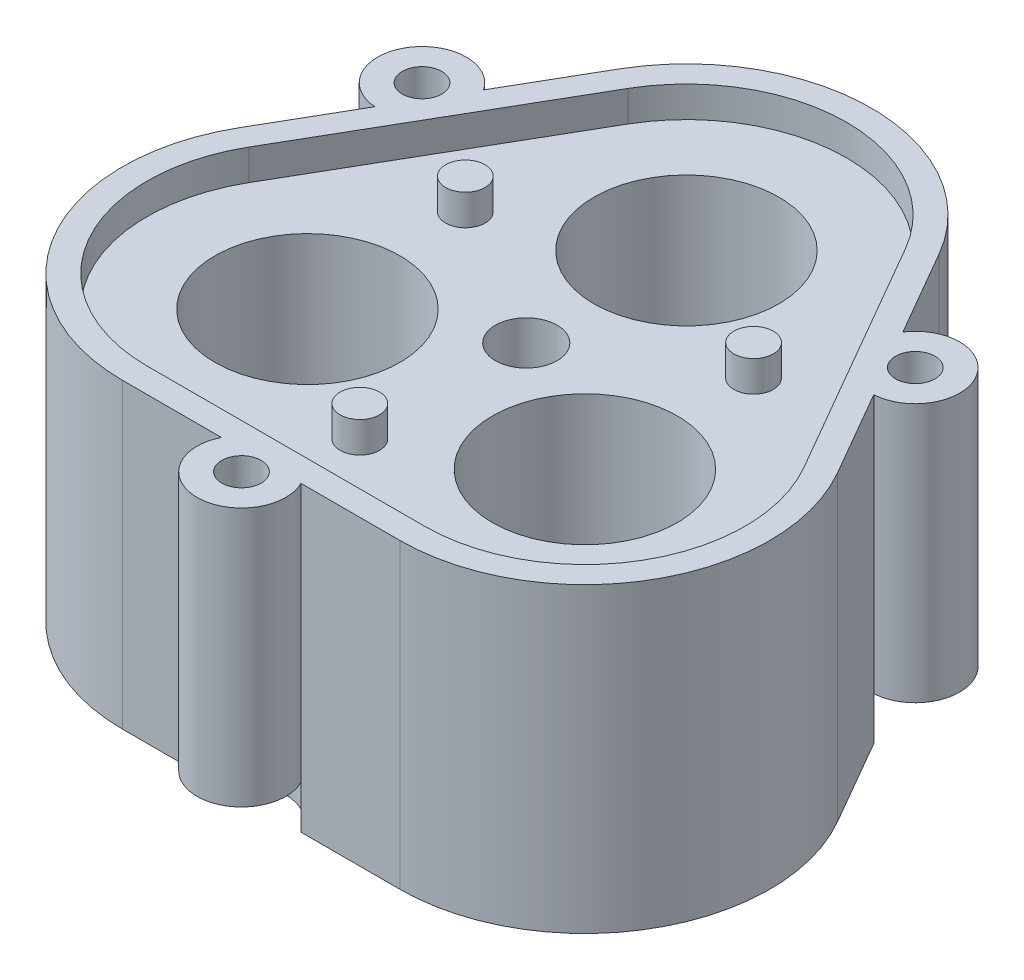
SolidWorks part; units mm, degrees
ref_plane "Front Plane" through (0, 0, 0) normal (0, 0, 1) x (1, 0, 0)
ref_plane "Top Plane" through (0, 0, 0) normal (0, 1, 0) x (1, 0, 0)
ref_plane "Right Plane" through (0, 0, 0) normal (1, 0, 0) x (0, 0, -1)
sketch "Sketch2" plane through (0, 0, 0) normal (0, 1, 0) x (1, 0, 0)
  line L0 (0, 0) -> (0, 12.9904) construction
  line L1 (0, 0) -> (11.25, -6.4952) construction
  line L2 (0, 0) -> (-11.25, -6.4952) construction
  line L3 (0, 12.9904) -> (-11.25, -6.4952) construction
  line L4 (-11.25, -6.4952) -> (11.25, -6.4952) construction
  line L5 (-11.25, -13.9952) -> (11.25, -13.9952) construction
  line L6 (6.4952, 16.7404) -> (17.7452, -2.7452) construction
  line L7 (-6.4952, 16.7404) -> (-17.7452, -2.7452) construction
  line L8 (-37.2308, -21.4952) -> (37.2308, -21.4952)
  line L9 (0, 42.9904) -> (-37.2308, -21.4952)
  line L10 (0, 42.9904) -> (37.2308, -21.4952)
  circle A0 centre (0, 12.9904) radius 7.5
  circle A1 centre (-11.25, -6.4952) radius 7.5
  circle A2 centre (11.25, -6.4952) radius 7.5
  circle A3 centre (0, 0) radius 2.5
  circle A4 centre (-11.25, -6.4952) radius 15 construction
  dimension "D3" = 15
  dimension "D9" = 5
  dimension "D10" = 30
  dimension "D1" = 120
  dimension "D2" = 120
  dimension "D4" = 22.5
  dimension "D5" = 7.5
  dimension "D6" = 7.5
  dimension "D7" = 7.5
  dimension "D8" = 74.4615
extrude "Boss-Extrude1" add sketch "Sketch2" along normal blind 12
sketch "Sketch4" plane through (0, 0, 0) normal (0, -1, 0) x (1, 0, 0)
  line L0 (-37.2308, 21.4952) -> (37.2308, 21.4952)
  line L1 (37.2308, 21.4952) -> (0, -42.9904)
  line L2 (0, -42.9904) -> (-37.2308, 21.4952)
  circle A0 centre (-11.25, 6.4952) radius 6
  circle A1 centre (11.25, 6.4952) radius 6
  circle A2 centre (0, -12.9904) radius 6
  circle A3 centre (0, 0) radius 2.5
  dimension "D1" = 12
  dimension "D2" = 5
extrude "Boss-Extrude2" add sketch "Sketch4" along normal blind 8
ref_plane "Plane1" through (0, -8, 0) normal (0, 1, 0) x (1, 0, 0)
sketch "Sketch7" plane through (0, -8, 0) normal (0, 1, 0) x (1, 0, 0)
  circle A0 centre (0, 12.9904) radius 4
  circle A1 centre (-11.25, -6.4952) radius 4
  circle A2 centre (11.25, -6.4952) radius 4
  dimension "D1" = 8
extrude "Boss-Extrude3" add sketch "Sketch7" along normal blind 8 separate body
sketch "Sketch9" plane through (0, -8, 0) normal (0, 1, 0) x (1, 0, 0)
  line L0 (0, 42.9904) -> (-37.2308, -21.4952)
  line L1 (-37.2308, -21.4952) -> (37.2308, -21.4952)
  line L2 (37.2308, -21.4952) -> (0, 42.9904)
extrude "Boss-Extrude4" add sketch "Sketch9" against normal blind 2
sketch "Sketch10" plane through (0, -8, 0) normal (0, 1, 0) x (1, 0, 0)
  line L0 (0, 0) -> (-11.25, -6.4952) construction
  line L1 (-11.25, -6.4952) -> (0, 12.9904) construction
  line L2 (0, 12.9904) -> (0, 0) construction
  line L3 (0, 0) -> (11.25, -6.4952) construction
  line L4 (11.25, -6.4952) -> (0, 12.9904) construction
  line L5 (-11.25, -6.4952) -> (11.25, -6.4952) construction
  line L6 (-11.25, -6.4952) -> (-12.6686, -1.7007) construction
  line L7 (-11.25, -6.4952) -> (-8.386, -2.3967) construction
  line L8 (-11.25, -6.4952) -> (-6.26, -6.179) construction
  line L9 (-11.25, -6.4952) -> (-7.8916, -10.1994) construction
  line L10 (-11.25, -6.4952) -> (-12.0521, -11.4304) construction
  line L11 (-11.25, -6.4952) -> (-15.6086, -8.9451) construction
  line L12 (-11.25, -6.4952) -> (-15.883, -4.615) construction
  line L13 (0, 12.9904) -> (4.8615, 11.8217) construction
  line L14 (0, 12.9904) -> (2.1174, 8.4608) construction
  line L15 (0, 12.9904) -> (-2.2212, 8.5108) construction
  line L16 (0, 12.9904) -> (-4.8871, 11.934) construction
  line L17 (0, 12.9904) -> (-3.873, 16.1527) construction
  line L18 (0, 12.9904) -> (0.0576, 17.99) construction
  line L19 (0, 12.9904) -> (3.9448, 16.0626) construction
  line L20 (11.25, -6.4952) -> (7.8071, -10.121) construction
  line L21 (11.25, -6.4952) -> (6.2686, -6.0641) construction
  line L22 (11.25, -6.4952) -> (8.4812, -2.3318) construction
  line L23 (11.25, -6.4952) -> (12.7787, -1.7346) construction
  line L24 (11.25, -6.4952) -> (15.9251, -4.7222) construction
  line L25 (11.25, -6.4952) -> (15.551, -9.0449) construction
  line L26 (11.25, -6.4952) -> (11.9382, -11.4476) construction
  circle A1 centre (-8.386, -2.3967) radius 0.75
  circle A4 centre (-11.25, -6.4952) radius 4 construction
  circle A5 centre (-11.25, -6.4952) radius 6 construction
  circle A6 centre (-11.25, -6.4952) radius 5 construction
  circle A7 centre (-12.6686, -1.7007) radius 0.75
  circle A8 centre (-6.26, -6.179) radius 0.75
  circle A9 centre (-7.8916, -10.1994) radius 0.75
  circle A10 centre (-12.0521, -11.4304) radius 0.75
  circle A11 centre (-15.6086, -8.9451) radius 0.75
  circle A12 centre (-15.883, -4.615) radius 0.75
  circle A13 centre (2.1174, 8.4608) radius 0.75
  circle A14 centre (4.8615, 11.8217) radius 0.75
  circle A15 centre (-2.2212, 8.5108) radius 0.75
  circle A16 centre (-4.8871, 11.934) radius 0.75
  circle A17 centre (-3.873, 16.1527) radius 0.75
  circle A18 centre (0.0576, 17.99) radius 0.75
  circle A19 centre (3.9448, 16.0626) radius 0.75
  circle A20 centre (0, 12.9904) radius 4 construction
  circle A21 centre (0, 12.9904) radius 6 construction
  circle A22 centre (0, 12.9904) radius 5 construction
  circle A23 centre (6.2686, -6.0641) radius 0.75
  circle A24 centre (7.8071, -10.121) radius 0.75
  circle A25 centre (8.4812, -2.3318) radius 0.75
  circle A26 centre (12.7787, -1.7346) radius 0.75
  circle A27 centre (15.9251, -4.7222) radius 0.75
  circle A28 centre (15.551, -9.0449) radius 0.75
  circle A29 centre (11.9382, -11.4476) radius 0.75
  circle A30 centre (11.25, -6.4952) radius 4 construction
  circle A31 centre (11.25, -6.4952) radius 6 construction
  circle A32 centre (11.25, -6.4952) radius 5 construction
  circle A33 centre (0, 0) radius 2.5
  point P27 (-11.25, -6.4952)
  point P47 (0, 12.9904)
  point P66 (11.25, -6.4952)
  point P67 (0, 0)
  dimension "D1" = 12
  dimension "D2" = 8
  dimension "D3" = 10
  dimension "D4" = 1.5
  dimension "D7" = 5
  dimension "D5" = 7
  dimension "D6" = 3
extrude "Cut-Extrude2" cut sketch "Sketch10" against normal through all both and the other way through all
ref_plane "Plane2" through (0, 12, 0) normal (0, 1, 0) x (1, 0, 0)
sketch "Sketch12" plane through (0, 12, 0) normal (0, 1, 0) x (1, 0, 0)
  line L0 (-12.9904, 20.4904) -> (-24.2404, 1.0048)
  line L4 (-11.25, -21.4952) -> (11.25, -21.4952)
  line L7 (24.2404, 1.0048) -> (12.9904, 20.4904)
  arc A0 (12.9904, 20.4904) -> (-12.9904, 20.4904) centre (0, 12.9904) ccw
  arc A1 (-24.2404, 1.0048) -> (-11.25, -21.4952) centre (-11.25, -6.4952) ccw
  arc A2 (11.25, -21.4952) -> (24.2404, 1.0048) centre (11.25, -6.4952) ccw
  circle A3 centre (0, 0) radius 57.2843
extrude "Cut-Extrude3" cut sketch "Sketch12" against normal through all both and the other way through all
sketch "Sketch13" plane through (0, 12, 0) normal (0, 1, 0) x (1, 0, 0)
  line L0 (-11.2583, 19.4904) -> (-22.5083, 0.0048)
  line L1 (-11.25, -19.4952) -> (11.25, -19.4952)
  line L2 (11.2583, 19.4904) -> (22.5083, 0.0048)
  line L3 (-12.9904, 20.4904) -> (-24.2404, 1.0048) construction
  line L5 (-11.25, -21.4952) -> (11.25, -21.4952)
  line L6 (24.2404, 1.0048) -> (12.9904, 20.4904)
  line L7 (-12.9904, 20.4904) -> (-24.2404, 1.0048)
  line L8 (0.0166, -0.0096) -> (-16.8833, 9.7476) construction
  arc A1 (-22.5083, 0.0048) -> (-11.25, -19.4952) centre (-11.25, -6.4952) ccw
  arc A2 (-0.0166, -0.0096) -> (0.0166, -0.0096) centre (0, 12.9904) ccw
  arc A3 (11.25, -19.4952) -> (22.5083, 0.0048) centre (11.25, -6.4952) ccw
  arc A4 (0.0166, -0.0096) -> (0, 0.0192) centre (-11.25, -6.4952) ccw
  arc A5 (0, 0.0192) -> (-0.0166, -0.0096) centre (11.25, -6.4952) ccw
  arc A6 (11.2583, 19.4904) -> (-11.2583, 19.4904) centre (0, 12.9904) ccw
  arc A8 (11.25, -21.4952) -> (24.2404, 1.0048) centre (11.25, -6.4952) ccw
  arc A9 (12.9904, 20.4904) -> (-12.9904, 20.4904) centre (0, 12.9904) ccw
  arc A10 (-24.2404, 1.0048) -> (-11.25, -21.4952) centre (-11.25, -6.4952) ccw
  circle A11 centre (-11.6872, 6.7476) radius 1.6
  circle A12 centre (11.6872, 6.7476) radius 1.6
  circle A13 centre (0, -13.4952) radius 1.6
  point P42 (0, 0)
  dimension "D2" = 13
  dimension "D3" = 3.2
  dimension "D1" = 2
  dimension "D4" = 6
  dimension "D5" = 3
sketch "Sketch15" plane through (0, -8, 0) normal (0, 1, 0) x (1, 0, 0)
  circle A0 centre (0, 12.9904) radius 1.6
  circle A1 centre (-11.25, -6.4952) radius 1.6
  circle A2 centre (11.25, -6.4952) radius 1.6
  dimension "D1" = 3.2
extrude "Cut-Extrude4" cut sketch "Sketch15" against normal through all both and the other way through all
extrude "Boss-Extrude5" add sketch "Sketch13" along normal blind 2.5 contours L7 A10 L5 A8 L6 A9 A6 L2 A3 L1 A1 L0 | A13 | A12 | A11
ref_plane "Plane3" through (0, 14.5, 0) normal (0, 1, 0) x (1, 0, 0)
sketch "Sketch16" plane through (0, 14.5, 0) normal (0, 1, 0) x (1, 0, 0)
  line L0 (0, 0) -> (-40.8337, 23.5754) construction
  line L11 (-12.9904, 20.4904) -> (-24.2404, 1.0048) construction
  circle A6 centre (-20.001, 11.5476) radius 1.6
  circle A7 centre (-20.001, 11.5476) radius 3.6
  circle A8 centre (20.001, 11.5476) radius 1.6
  circle A9 centre (20.001, 11.5476) radius 3.6
  circle A10 centre (0, -23.0952) radius 1.6
  circle A11 centre (0, -23.0952) radius 3.6
  point P16 (0, 0)
  point P26 (1.0392, -1.8)
  dimension "D1" = 3.2
  dimension "D3" = 3
  dimension "D2" = 2
extrude "Boss-Extrude6" add sketch "Sketch16" against normal blind 21
ref_plane "Plane4" through (0, -10, 0) normal (0, 1, 0) x (1, 0, 0)
sketch "Sketch19" plane through (0, -10, 0) normal (0, 1, 0) x (1, 0, 0)
  circle A0 centre (20.001, 11.5476) radius 1.6
  circle A1 centre (20.001, 11.5476) radius 3.6
extrude "Cut-Extrude10" cut sketch "Sketch19" along normal up to surface (3.5 mm away) and the other way through all up to face at (20.0876, -6.5, -11.1976)
pattern_circular "CirPattern1" count 3 over 360 about axis through (0, 0, 0) along (0, 1, 0) of "Cut-Extrude10"
